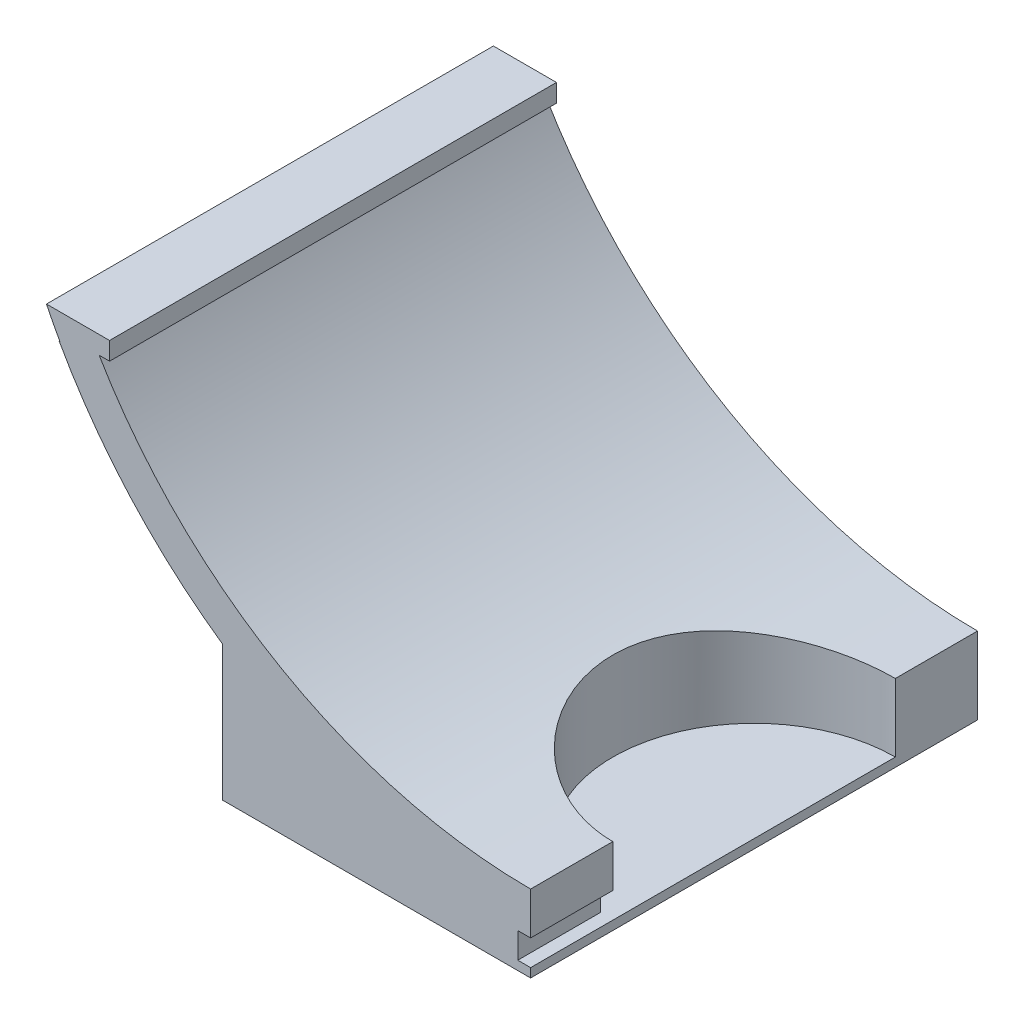
SolidWorks part; units mm, degrees
ref_plane "前视基准面" through (0, 0, 0) normal (0, 0, 1) x (1, 0, 0)
ref_plane "上视基准面" through (0, 0, 0) normal (0, 1, 0) x (1, 0, 0)
ref_plane "右视基准面" through (0, 0, 0) normal (1, 0, 0) x (0, 0, -1)
sketch "草图1" plane through (0, 0, 0) normal (0, 0, 1) x (1, 0, 0)
  arc A0 (-203, 0) -> (203, 0) centre (0, 0) ccw
  arc A1 (-210, 0) -> (210, 0) centre (0, 0) ccw
  arc A2 (-203, 0) -> (203, 0) centre (0, 0) ccw
  circle A3 centre (0, 0) radius 210
  circle A4 centre (0, 0) radius 203
  point P12 (0, 0)
extrude "凸台-拉伸2" add sketch "草图1" along normal blind 174
sketch "草图2" plane through (0, 0, 174) normal (0, 0, 1) x (1, 0, 0)
  line L0 (-173.7354, -102) -> (-170.7354, -102)
  line L1 (-170.7354, -102) -> (-170.7354, -105)
  line L2 (-170.7354, -105) -> (-173.7354, -105)
  line L3 (173.7354, -102) -> (170.7354, -102)
  line L4 (-173.7354, -102) -> (-175.5135, -102)
  line L6 (173.7354, -102) -> (175.5135, -102)
  line L7 (173.7354, -105) -> (170.7354, -105)
  line L8 (170.7354, -105) -> (170.7354, -102)
  circle A0 centre (0, 0) radius 203 construction
  arc A1 (0, -203) -> (-173.7354, -105) centre (0, 0) ccw
  circle M4 centre (0, 0) radius 203
extrude "凸台-拉伸4" add sketch "草图2" against normal up to surface (174 mm away) contours L0 L4 L2 L1 M4 | L8 L7 L6 L3 M4 up to face at (203, 0, 0)
sketch "草图3" plane through (0, 0, 174) normal (0, 0, 1) x (1, 0, 0)
  line L0 (-170.7354, -102) -> (238.3336, -102)
  line L1 (238.3336, -102) -> (254.3342, 272.2925)
  line L2 (254.3342, 272.2925) -> (-334.5694, 221.8511)
  line L3 (-170.7354, -102) -> (-306.8306, -102)
  line L4 (-306.8306, -102) -> (-334.5694, 221.8511)
extrude "切除-拉伸1" cut sketch "草图3" against normal blind 654
ref_plane "基准面1" through (0, -209.75, 0) normal (0, 1, 0) x (1, 0, 0)
sketch "草图5" plane through (0, 0, 174) normal (0, 0, 1) x (1, 0, 0)
  line L0 (0, -209.75) -> (120, -209.75)
  line L1 (95.7, -209.75) -> (-95.7, -209.75) construction
  line L2 (120, -209.75) -> (120, -172.0322)
  line L3 (0, -209.75) -> (-120, -209.75)
  line L4 (-120, -209.75) -> (-120, -172.0322)
  arc A0 (-120, -172.0322) -> (120, -172.0322) centre (0, 0) ccw
  arc M3 (-183.5647, -102) -> (183.5647, -102) centre (0, 0) ccw
extrude "凸台-拉伸5" add sketch "草图5" against normal up to surface (174 mm away) contours L4 L3 M3 | L0 L2 M3 up to face at (0, -129.25, 0)
sketch "草图6" plane through (0, 0, 174) normal (0, 0, 1) x (1, 0, 0)
  line L0 (-175.5135, -102) -> (-166.1957, -102)
  line L1 (175.5135, -102) -> (166.1957, -102)
  arc A0 (-166.1957, -102) -> (166.1957, -102) centre (0, 0) ccw
  arc A1 (-175.5135, -102) -> (175.5135, -102) centre (0, 0) ccw
extrude "凸台-拉伸6" add sketch "草图6" against normal up to surface (174 mm away) up to face at (0, -151.228, 0)
sketch "草图7" plane through (0, 0, 174) normal (0, 0, 1) x (1, 0, 0)
  line L0 (-166.9331, -92) -> (-166.9331, -95)
  line L1 (171.9331, -92) -> (166.9331, -92)
  line L2 (-171.9331, -92) -> (-166.9331, -92)
  line L3 (-188.4969, -92) -> (-171.9331, -92)
  line L4 (171.9331, -92) -> (188.4969, -92)
  line L5 (-166.9331, -95) -> (-170.2939, -95)
  line L6 (166.9331, -92) -> (166.9331, -95)
  line L7 (166.9331, -95) -> (170.2939, -95)
  arc A1 (-188.4969, -92) -> (188.4969, -92) centre (0, 0) ccw
  arc A2 (-170.2939, -95) -> (170.2939, -95) centre (0, 0) ccw
extrude "凸台-拉伸7" add sketch "草图7" against normal up to surface (174 mm away) up to face at (0, -169.2192, 0)
sketch "草图8" plane through (0, 0, 0) normal (0, 0, -1) x (-1, 0, 0)
  line L0 (166.9331, -92) -> (163.9331, -92)
  line L1 (163.9331, -92) -> (163.9331, -99)
  line L2 (163.9331, -99) -> (168, -99)
  line L3 (166.9331, -92) -> (166.9331, -95)
  line L4 (166.9331, -95) -> (170.2939, -95)
  line L6 (-166.9331, -95) -> (-170.2939, -95)
  line L7 (-166.9331, -92) -> (-166.9331, -95)
  line L8 (-163.9331, -99) -> (-168, -99)
  line L9 (-163.9331, -92) -> (-163.9331, -99)
  line L10 (-166.9331, -92) -> (-163.9331, -92)
  arc A0 (-170.2939, -95) -> (170.2939, -95) centre (0, 0) ccw construction
  arc A1 (168, -99) -> (170.2939, -95) centre (0, 0) ccw
  arc A2 (-168, -99) -> (-170.2939, -95) centre (0, 0) cw
extrude "凸台-拉伸8" add sketch "草图8" against normal up to surface (174 mm away) up to face at (0, -135.959, 174)
sketch "草图9" plane through (0, 0, 174) normal (0, 0, 1) x (1, 0, 0)
  line L0 (0, -195) -> (0, -225)
  line L1 (0, -225) -> (120, -225)
  line L2 (120, -225) -> (120, -209.75)
  line L3 (120, -209.75) -> (-120, -209.75)
  line L4 (-120, -209.75) -> (-120, -225)
  line L5 (-120, -225) -> (18.0074, -225)
  arc A2 (-168, -99) -> (168, -99) centre (0, 0) ccw construction
  line M11 (-120, -209.75) -> (-10.2439, -209.75)
  arc M12 (-10.2439, -209.75) -> (10.2439, -209.75) centre (0, 0) ccw
  line M13 (10.2439, -209.75) -> (120, -209.75)
extrude "凸台-拉伸9" add sketch "草图9" against normal up to vertex (174 mm away) contours L1 L2 L0 M13 M12 | L4 L5 L0 M12 M11 up to point (120, -209.75, 0)
sketch "草图10" plane through (0, 0, 174) normal (0, 0, 1) x (1, 0, 0)
  line L0 (-5, -221.5) -> (-5, -211.5)
  line L2 (0, -211.5) -> (5, -211.5)
  line L3 (-55, -195) -> (-55, -221.5)
  line L4 (-5, -211.5) -> (0, -211.5)
  line L8 (5, -211.5) -> (5, -221.5)
  line L9 (5, -221.5) -> (-5, -221.5)
sketch "草图11" plane through (0, 0, 0) normal (0, 1, 0) x (1, 0, 0)
  line L0 (-163.9331, -87) -> (188.4969, -87)
  line L1 (-163.9331, -174) -> (-163.9331, 0) construction
  line L2 (188.4969, 0) -> (188.4969, -174) construction
  line L3 (0, 0) -> (0, -137.3076)
  circle A0 centre (0, -87) radius 55
extrude "切除-拉伸4" cut sketch "草图11" against normal up to vertex (221.5 mm away) up to point (-55, -221.5, 174)
extrude "切除-拉伸5" cut sketch "草图10" against normal blind 87 contours L9 L8 L2 L4 L0
sketch "草图12" plane through (0, 0, 0) normal (1, 0, 0) x (0, 0, -1)
  line L1 (400.8625, 124.1202) -> (-267.4328, 124.1202)
  line L2 (400.8625, 124.1202) -> (400.8625, -261.0344)
  line L3 (400.8625, -261.0344) -> (-267.4328, -261.0344)
  line L4 (-267.4328, 124.1202) -> (-267.4328, -261.0344)
  line L5 (400.8625, 124.1202) -> (-267.4328, -261.0344) construction
  line L6 (400.8625, -261.0344) -> (-267.4328, 124.1202) construction
  point P0 (66.7148, -68.4571)
extrude "切除-拉伸6" cut sketch "草图12" along normal blind 280
